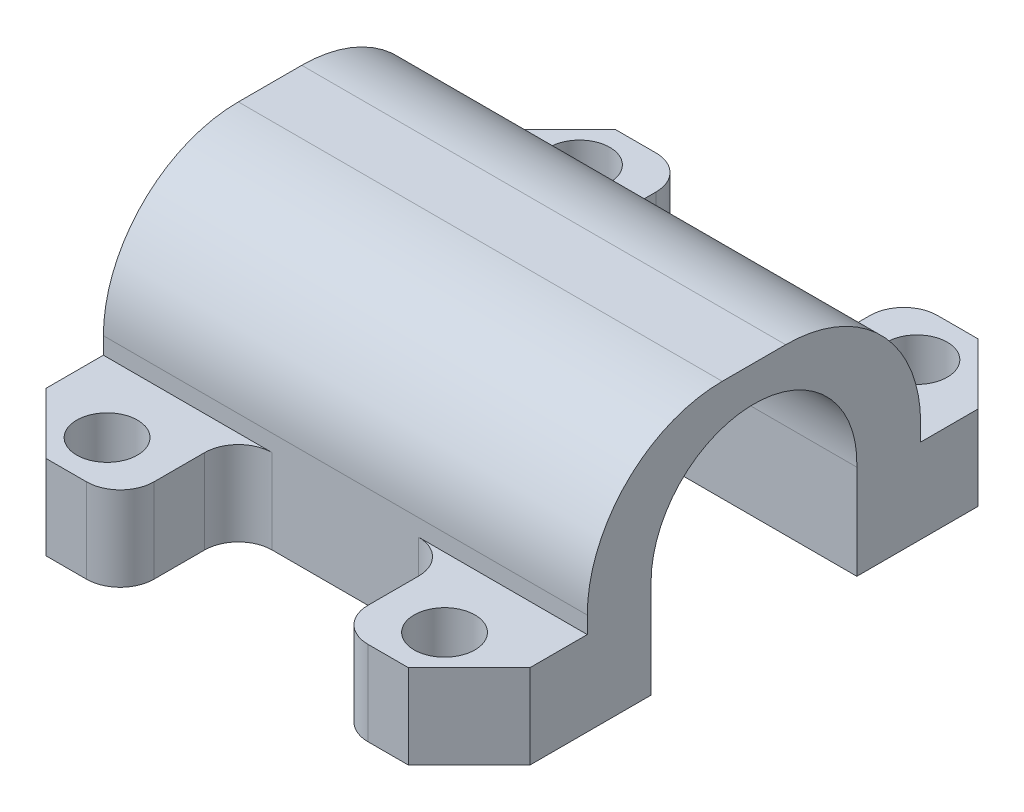
SolidWorks part; units mm, degrees
ref_plane "Front Plane" through (0, 0, 0) normal (0, 0, 1) x (1, 0, 0)
ref_plane "Top Plane" through (0, 0, 0) normal (0, 1, 0) x (1, 0, 0)
ref_plane "Right Plane" through (0, 0, 0) normal (1, 0, 0) x (0, 0, -1)
sketch "Sketch1" plane through (0, 0, 0) normal (0, 1, 0) x (1, 0, 0)
  line L0 (26.4739, -52.0178) -> (24.6739, -53.8178)
  line L1 (24.6739, -53.8178) -> (13.9339, -53.8178)
  line L2 (13.9339, -53.8178) -> (12.1339, -52.0178)
  line L3 (12.1339, -52.0178) -> (12.1339, -38.7393)
  line L4 (12.1339, -38.7393) -> (13.9339, -36.9393)
  line L5 (13.9339, -36.9393) -> (24.6739, -36.9393)
  line L6 (24.6739, -36.9393) -> (26.4739, -38.7393)
  line L7 (26.4739, -38.7393) -> (26.4739, -52.0178)
  dimension "D1" = 10.74
  dimension "D2" = 10.74
  dimension "D3" = 1.8
  dimension "D4" = 1.8
  dimension "D5" = 135
  dimension "D6" = 1.8
extrude "Boss-Extrude1" add sketch "Sketch1" along normal blind 2.5
sketch "Sketch2" plane through (0, 2.5, 0) normal (0, 1, 0) x (1, 0, 0)
  line L0 (12.1339, -38.7393) -> (12.1339, -52.0178) construction
  line L1 (26.4739, -52.0178) -> (26.4739, -38.7393) construction
  line L2 (13.9339, -53.8178) -> (24.6739, -53.8178) construction
  line L3 (24.6739, -36.9393) -> (13.9339, -36.9393) construction
  circle A0 centre (24.3039, -52.3778) radius 0.9
  circle A1 centre (14.3039, -52.3778) radius 0.9
  circle A2 centre (14.3039, -38.3793) radius 0.9
  circle A3 centre (24.3039, -38.3793) radius 0.9
  dimension "D1" = 1.8
  dimension "D2" = 1.8
  dimension "D3" = 1.8
  dimension "D4" = 1.8
  dimension "D5" = 2.17
  dimension "D6" = 2.17
  dimension "D7" = 2.17
  dimension "D8" = 2.17
  dimension "D9" = 1.44
  dimension "D10" = 1.44
  dimension "D11" = 1.44
  dimension "D12" = 1.44
extrude "Cut-Extrude1" cut sketch "Sketch2" against normal blind 2.5
sketch "Sketch3" plane through (0, 2.5, 0) normal (0, 1, 0) x (1, 0, 0)
  line L0 (26.4739, -52.0178) -> (26.4739, -38.7393) construction
  line L1 (26.4739, -50.3178) -> (12.1339, -50.3178)
  line L2 (26.4739, -50.3178) -> (26.4739, -40.4393)
  line L3 (26.4739, -40.4393) -> (12.1339, -40.4393)
  line L4 (12.1339, -50.3178) -> (12.1339, -40.4393)
  line L5 (12.1339, -38.7393) -> (12.1339, -52.0178) construction
  line L6 (13.9339, -53.8178) -> (24.6739, -53.8178) construction
  line L7 (24.6739, -36.9393) -> (13.9339, -36.9393) construction
  dimension "D1" = 3.5
  dimension "D2" = 3.5
extrude "Boss-Extrude2" add sketch "Sketch3" along normal blind 4.5
sketch "Sketch4" plane through (12.1339, 0, 0) normal (-1, 0, 0) x (0, 0, 1)
  line L0 (38.7393, 0) -> (52.0178, 0) construction
  line L1 (50.3178, 7) -> (50.3178, 2.5) construction
  circle A0 centre (45.3778, 2.9) radius 3.05
  dimension "D1" = 6.1
  dimension "D2" = 2.9
  dimension "D3" = 4.94
extrude "Cut-Extrude2" cut sketch "Sketch4" against normal through all
sketch "Sketch5" plane through (12.1339, 0, 0) normal (-1, 0, 0) x (0, 0, 1)
  line L7 (38.7393, 0) -> (44.433, 0) construction
  line L8 (42.3293, 0) -> (48.4278, 0)
  line L9 (42.3293, 0) -> (42.3293, 2.9)
  line L10 (42.3293, 2.9) -> (48.4278, 2.9)
  line L11 (48.4278, 0) -> (48.4278, 2.9)
  line L12 (50.3178, 7) -> (50.3178, 2.5) construction
  line L13 (40.4393, 7) -> (40.4393, 2.5) construction
  dimension "D1" = 1.89
  dimension "D2" = 1.89
  dimension "D3" = 2.9
extrude "Cut-Extrude3" cut sketch "Sketch5" against normal through all
fillet "Fillet1" radius 4 2 edges at (19.3039, 7, 40.4393) (19.3039, 7, 50.3178)
sketch "Sketch7" plane through (0, 2.5, 0) normal (0, 1, 0) x (1, 0, 0)
  line L0 (13.9339, -53.8178) -> (24.6739, -53.8178) construction
  line L1 (22.4739, -53.8178) -> (16.1339, -53.8178)
  line L2 (22.4739, -53.8178) -> (22.4739, -50.3178)
  line L3 (22.4739, -50.3178) -> (16.1339, -50.3178)
  line L4 (16.1339, -53.8178) -> (16.1339, -50.3178)
  line L5 (26.4739, -50.3178) -> (12.1339, -50.3178) construction
  line L6 (24.6739, -36.9393) -> (13.9339, -36.9393) construction
  line L7 (22.4739, -36.9393) -> (16.1339, -36.9393)
  line L8 (22.4739, -36.9393) -> (22.4739, -40.4393)
  line L9 (22.4739, -40.4393) -> (16.1339, -40.4393)
  line L10 (16.1339, -36.9393) -> (16.1339, -40.4393)
  line L11 (12.1339, -40.4393) -> (26.4739, -40.4393) construction
  line L12 (26.4739, -40.4393) -> (26.4739, -38.7393) construction
  line L13 (12.1339, -38.7393) -> (12.1339, -40.4393) construction
  line L14 (26.4739, -52.0178) -> (26.4739, -50.3178) construction
  line L15 (12.1339, -50.3178) -> (12.1339, -52.0178) construction
  dimension "D1" = 4
  dimension "D2" = 4
  dimension "D3" = 4
  dimension "D4" = 4
extrude "Cut-Extrude5" cut sketch "Sketch7" against normal through all
fillet "Fillet2" radius 1 8 edges at (16.1339, 1.25, 50.3178) (16.1339, 1.25, 53.8178) (22.4739, 1.25, 50.3178) (22.4739, 1.25, 53.8178) (22.4739, 1.25, 40.4393) (16.1339, 1.25, 40.4393) (16.1339, 1.25, 36.9393) (22.4739, 1.25, 36.9393)
